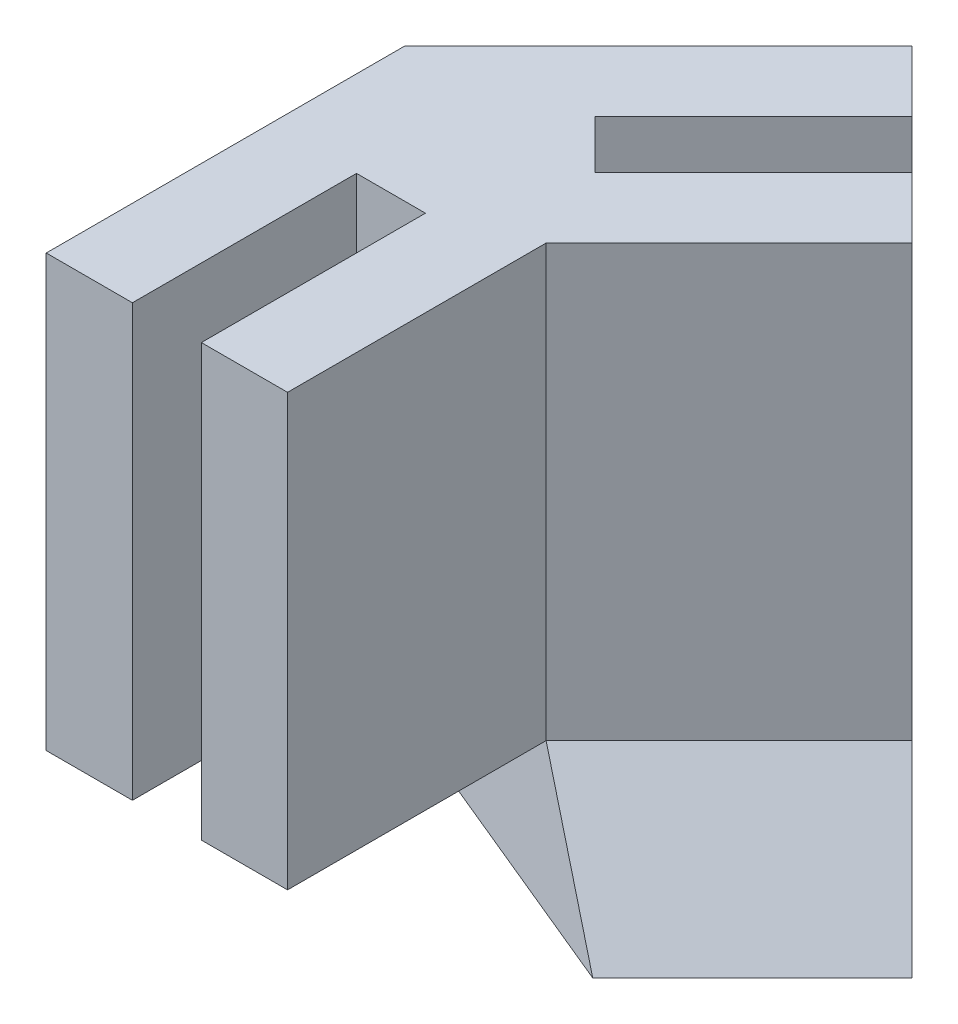
SolidWorks part; units mm, degrees
ref_plane "Front Plane" through (0, 0, 0) normal (0, 0, 1) x (1, 0, 0)
ref_plane "Top Plane" through (0, 0, 0) normal (0, 1, 0) x (1, 0, 0)
ref_plane "Right Plane" through (0, 0, 0) normal (1, 0, 0) x (0, 0, -1)
sketch "Sketch2" plane through (0, 0, 0) normal (0, 1, 0) x (1, 0, 0)
  line L0 (0, 0) -> (0, -15)
  line L1 (0, -15) -> (-5, -15)
  line L2 (-5, -15) -> (-5, -2)
  line L3 (-5, -2) -> (-9, -2)
  line L4 (-9, -2) -> (-9, -15)
  line L5 (-9, -15) -> (-14, -15)
  line L6 (0, 0) -> (-14, 5.799)
  line L7 (-14, -15) -> (-14, 5.799)
extrude "Boss-Extrude1" add sketch "Sketch2" along normal blind 25
ref_plane "Plane1" through (0, 0, 0) normal (0.3827, 0, -0.9239) x (-0.9239, 0, -0.3827)
mirror "Mirror1" about plane through (0, 25, 0) normal (-0.3827, 0, 0.9239) of "Boss-Extrude1"
sketch "Sketch4" plane through (0, 0, 0) normal (0.3827, 0, -0.9239) x (-0.9239, 0, -0.3827)
  line L0 (0, 0) -> (-5, -8.6603)
  line L1 (15.1535, 0) -> (10.1535, -8.6603)
  line L2 (10.1535, -8.6603) -> (-5, -8.6603)
  line L3 (15.1535, 0) -> (0, 0)
ref_plane "Plane2" through (10.6066, 0, -10.6066) normal (0.7071, 0, -0.7071) x (-0.7071, 0, -0.7071)
extrude "Boss-Extrude3" add sketch "Sketch4" along direction (0.7071, 0, -0.7071) on the side of the normal up to surface (18.8856 mm away) up to plane "Plane2"
